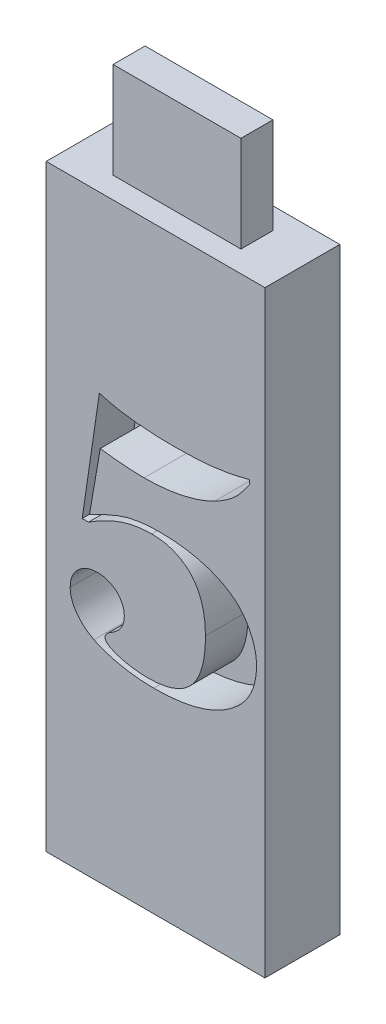
SolidWorks part; units mm, degrees
ref_plane "Front Plane" through (0, 0, 0) normal (0, 0, 1) x (1, 0, 0)
ref_plane "Top Plane" through (0, 0, 0) normal (0, 1, 0) x (1, 0, 0)
ref_plane "Right Plane" through (0, 0, 0) normal (1, 0, 0) x (0, 0, -1)
sketch "Sketch1" plane through (0, 0, 0) normal (0, 0, 1) x (1, 0, 0)
  line L1 (-8.69, -23.749) -> (8.69, -23.749)
  line L2 (-8.69, -23.749) -> (-8.69, 23.749)
  line L3 (-8.69, 23.749) -> (8.69, 23.749)
  line L4 (8.69, -23.749) -> (8.69, 23.749)
  line L5 (-8.69, -23.749) -> (8.69, 23.749) construction
  line L6 (-8.69, 23.749) -> (8.69, -23.749) construction
  point P0 (0, 0)
  dimension "D1" = 17.38
  dimension "D2" = 47.498
extrude "Boss-Extrude1" add sketch "Sketch1" along normal blind 5.95
sketch "Sketch2" plane through (0, 0, 5.95) normal (0, 0, 1) x (1, 0, 0)
  line L0 (0, 23.749) -> (0, -23.749) construction
  line L1 (8.69, 23.749) -> (-8.69, 23.749) construction
  line L2 (-8.69, -23.749) -> (8.69, -23.749) construction
  line L3 (0, -23.749) -> (0, 0) construction
  line L4 (0, 0) -> (-8.69, 0) construction
  line L5 (-8.69, 23.749) -> (-8.69, -23.749) construction
  line L6 (-8.69, 0) -> (8.69, 0) construction
  line L7 (8.69, -23.749) -> (8.69, 23.749) construction
  line L8 (-8.69, -23.749) -> (8.69, -23.749) construction
  line L9 (-8.69, -21.209) -> (8.69, -21.209) construction
  line L10 (-8.69, -18.669) -> (8.69, -18.669) construction
  line L11 (-8.69, -16.129) -> (8.69, -16.129) construction
  line L12 (-8.69, -13.589) -> (8.69, -13.589) construction
  line L13 (-8.69, -11.049) -> (8.69, -11.049) construction
  line L14 (-8.69, -8.509) -> (8.69, -8.509) construction
  line L15 (-8.69, -5.969) -> (8.69, -5.969) construction
  line L16 (-8.69, -3.429) -> (8.69, -3.429) construction
  line L17 (-8.69, -0.889) -> (8.69, -0.889) construction
  line L18 (-8.69, 1.651) -> (8.69, 1.651) construction
  line L19 (-8.69, 4.191) -> (8.69, 4.191) construction
  line L20 (-8.69, 6.731) -> (8.69, 6.731) construction
  line L21 (-8.69, 9.271) -> (8.69, 9.271) construction
  line L22 (-8.69, 11.811) -> (8.69, 11.811) construction
  line L23 (-8.69, 14.351) -> (8.69, 14.351) construction
  line L24 (-8.69, 16.891) -> (8.69, 16.891) construction
  line L25 (-8.69, 19.431) -> (8.69, 19.431) construction
  line L26 (-8.69, 21.971) -> (8.69, 21.971) construction
  line L27 (-8.69, 23.749) -> (-8.69, -23.749) construction
  line L28 (-6.15, 23.749) -> (-6.15, -23.749) construction
  line L29 (-3.61, 23.749) -> (-3.61, -23.749) construction
  line L30 (-1.07, 23.749) -> (-1.07, -23.749) construction
  line L31 (1.47, 23.749) -> (1.47, -23.749) construction
  line L32 (4.01, 23.749) -> (4.01, -23.749) construction
  line L33 (6.55, 23.749) -> (6.55, -23.749) construction
  text T0 "5\r\n" font "Engravers MT" height in points 72
  dimension "D1" = 19
  dimension "D2" = 2.54
  dimension "D4" = 2.54
  dimension "D3" = 7
extrude "Cut-Extrude1" cut sketch "Sketch2" against normal blind 3.41
sketch "Sketch3" plane through (0, 23.749, 0) normal (0, 1, 0) x (1, 0, 0)
  line L0 (0, 0) -> (0, -5.95) construction
  line L1 (8.69, -5.95) -> (-8.69, -5.95) construction
  line L2 (0, -5.95) -> (0, -2.975) construction
  line L3 (0, -2.975) -> (-8.69, -2.975) construction
  line L4 (-8.69, -5.95) -> (-8.69, 0) construction
  line L5 (-8.69, -2.975) -> (8.69, -2.975) construction
  line L6 (8.69, -5.95) -> (8.69, 0) construction
  line L8 (-5.08, -4.245) -> (5.08, -4.245)
  line L9 (-5.08, -4.245) -> (-5.08, -1.705)
  line L10 (-5.08, -1.705) -> (5.08, -1.705)
  line L11 (5.08, -4.245) -> (5.08, -1.705)
  line L12 (-5.08, -4.245) -> (5.08, -1.705) construction
  line L13 (-5.08, -1.705) -> (5.08, -4.245) construction
  dimension "D1" = 2.54
  dimension "D2" = 10.16
extrude "Boss-Extrude2" add sketch "Sketch3" along normal blind 7.62
